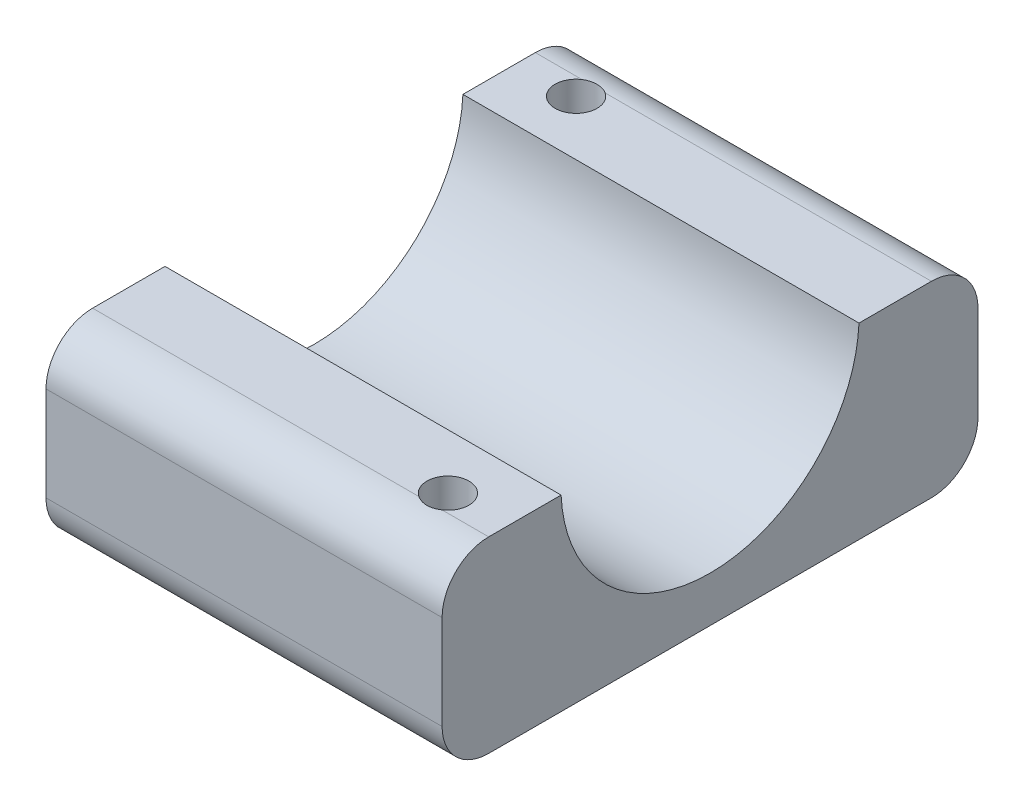
SolidWorks part; units mm, degrees
ref_plane "Front Plane" through (0, 0, 0) normal (0, 0, 1) x (1, 0, 0)
ref_plane "Top Plane" through (0, 0, 0) normal (0, 1, 0) x (1, 0, 0)
ref_plane "Right Plane" through (0, 0, 0) normal (1, 0, 0) x (0, 0, -1)
sketch "Sketch1" plane through (0, 0, 0) normal (1, 0, 0) x (0, 0, -1)
  line L0 (-19, -16.7) -> (19, -16.7)
  line L1 (23, -12.7) -> (23, -4.6)
  line L2 (19, -0.6) -> (-19, -0.6)
  line L3 (-23, -4.6) -> (-23, -12.7)
  arc A0 (19, -16.7) -> (23, -12.7) centre (19, -12.7) ccw
  arc A1 (23, -4.6) -> (19, -0.6) centre (19, -4.6) ccw
  arc A2 (-19, -0.6) -> (-23, -4.6) centre (-19, -4.6) ccw
  arc A3 (-23, -12.7) -> (-19, -16.7) centre (-19, -12.7) ccw
extrude "Boss-Extrude1" add sketch "Sketch1" along normal mid plane 34
sketch "Sketch2" plane through (0, 0, 0) normal (1, 0, 0) x (0, 0, -1)
  circle A0 centre (0, 0) radius 12.8
extrude "Cut-Extrude1" cut sketch "Sketch2" against normal through all and the other way through all
ref_plane "Plane1" through (0, -16.7, 0) normal (0, 1, 0) x (1, 0, 0)
sketch "Sketch3" plane through (0, -16.7, 0) normal (0, 1, 0) x (1, 0, 0)
  circle A0 centre (12, -17.5) radius 1.8
  circle A1 centre (-12, 17.5) radius 1.8
extrude "Cut-Extrude2" cut sketch "Sketch3" along normal blind 17
ref_plane "Plane2" through (0, -16.7, 0) normal (0, 1, 0) x (1, 0, 0)
sketch "Sketch4" plane through (0, -16.7, 0) normal (0, 1, 0) x (1, 0, 0)
  circle A0 centre (12, -17.5) radius 3.25
  circle A1 centre (-12, 17.5) radius 3.25
extrude "Cut-Extrude3" cut sketch "Sketch4" along normal blind 7.5
